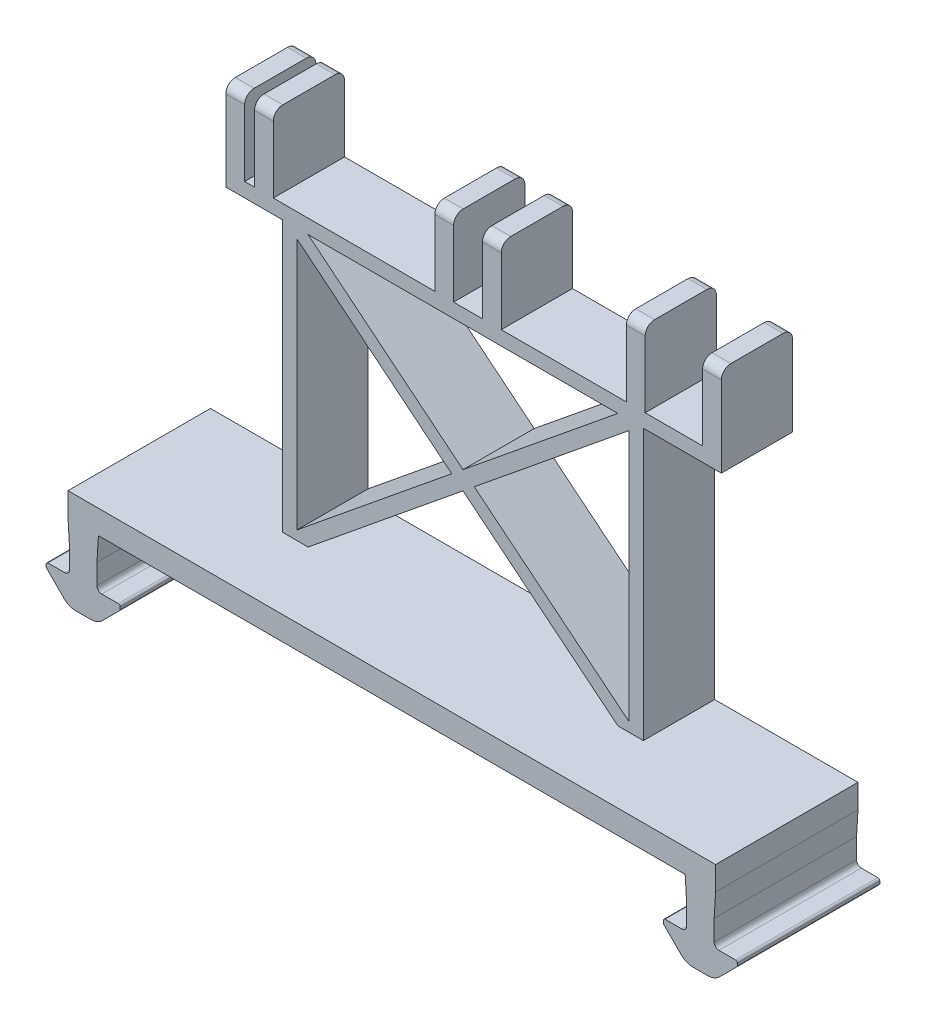
SolidWorks part; units mm, degrees
ref_plane "Front Plane" through (0, 0, 0) normal (0, 0, 1) x (1, 0, 0)
ref_plane "Top Plane" through (0, 0, 0) normal (0, 1, 0) x (1, 0, 0)
ref_plane "Right Plane" through (0, 0, 0) normal (1, 0, 0) x (0, 0, -1)
sketch "Sketch1" plane through (0, 0, 0) normal (0, 0, 1) x (1, 0, 0)
  line L7 (0, 0) -> (0, 26.663) construction
  line L8 (-2.0169, 6.858) -> (2.0169, 6.858)
  line L9 (5.3755, 8.2492) -> (10.0266, 12.9003)
  line L10 (10.287, 13.5289) -> (10.287, 14.0979)
  line L11 (9.398, 14.9869) -> (4.953, 14.9869)
  line L12 (4.064, 15.8759) -> (4.064, 27.6869)
  line L13 (0, 0) -> (20.2214, 20.2214) construction
  line L14 (-4.064, 15.8759) -> (-4.064, 27.6869)
  line L15 (-9.398, 14.9869) -> (-4.953, 14.9869)
  line L16 (-10.287, 13.5289) -> (-10.287, 14.0979)
  line L17 (-5.3755, 8.2492) -> (-10.0266, 12.9003)
  line L19 (163.0831, 6.858) -> (167.1169, 6.858)
  line L20 (170.4755, 8.2492) -> (175.1266, 12.9003)
  line L21 (175.387, 13.5289) -> (175.387, 14.0979)
  line L22 (174.498, 14.9869) -> (170.053, 14.9869)
  line L23 (169.164, 15.8759) -> (169.164, 27.6869)
  line L24 (161.036, 15.8759) -> (161.036, 27.6869)
  line L25 (155.702, 14.9869) -> (160.147, 14.9869)
  line L26 (154.813, 13.5289) -> (154.813, 14.0979)
  line L27 (159.7245, 8.2492) -> (155.0734, 12.9003)
  line L29 (-4.064, 27.6869) -> (-4.064, 34.0369)
  line L30 (-4.064, 34.0369) -> (169.164, 34.0369)
  line L31 (169.164, 34.0369) -> (169.164, 27.6869)
  line L32 (4.064, 27.6869) -> (161.036, 27.6869)
  arc A0 (10.0266, 12.9003) -> (10.287, 13.5289) centre (9.398, 13.5289) ccw
  arc A1 (9.398, 14.9869) -> (10.287, 14.0979) centre (9.398, 14.0979) cw
  arc A2 (4.953, 14.9869) -> (4.064, 15.8759) centre (4.953, 15.8759) cw
  arc A3 (2.0169, 6.858) -> (5.3755, 8.2492) centre (2.0169, 11.6078) ccw
  arc A4 (-2.0169, 6.858) -> (-5.3755, 8.2492) centre (-2.0169, 11.6078) cw
  arc A5 (-4.953, 14.9869) -> (-4.064, 15.8759) centre (-4.953, 15.8759) ccw
  arc A6 (-9.398, 14.9869) -> (-10.287, 14.0979) centre (-9.398, 14.0979) ccw
  arc A7 (-10.0266, 12.9003) -> (-10.287, 13.5289) centre (-9.398, 13.5289) cw
  arc A8 (175.1266, 12.9003) -> (175.387, 13.5289) centre (174.498, 13.5289) ccw
  arc A9 (174.498, 14.9869) -> (175.387, 14.0979) centre (174.498, 14.0979) cw
  arc A10 (170.053, 14.9869) -> (169.164, 15.8759) centre (170.053, 15.8759) cw
  arc A11 (167.1169, 6.858) -> (170.4755, 8.2492) centre (167.1169, 11.6078) ccw
  arc A12 (163.0831, 6.858) -> (159.7245, 8.2492) centre (163.0831, 11.6078) cw
  arc A13 (160.147, 14.9869) -> (161.036, 15.8759) centre (160.147, 15.8759) ccw
  arc A14 (155.702, 14.9869) -> (154.813, 14.0979) centre (155.702, 14.0979) ccw
  arc A15 (155.0734, 12.9003) -> (154.813, 13.5289) centre (155.702, 13.5289) cw
  point P1 (-4.064, 14.9869)
  point P20 (4.064, 14.9869)
  point P34 (0, 6.858)
  point P36 (161.036, 14.9869)
  point P63 (165.1, 6.858)
  dimension "D6" = 0.889
  dimension "D9" = 4.7498
  dimension "D1" = 12.7
  dimension "D2" = 4.064
  dimension "D3" = 6.858
  dimension "D4" = 10.287
  dimension "D5" = 2.032
  dimension "D7" = 0.569
  dimension "D8" = 45
  dimension "D11" = 165.1
  dimension "D12" = 6.35
  dimension "D10" = 2
extrude "Boss-Extrude2" add sketch "Sketch1" along normal blind 38.1
sketch "Sketch7" plane through (0, 0, 0) normal (0, 0, 1) x (1, 0, 0)
  line L0 (82.55, 68.2701) -> (82.55, 42.7511) construction
  line L1 (130.81, 106.4269) -> (169.164, 106.4269)
  line L3 (169.164, 34.0369) -> (-4.064, 34.0369) construction
  line L4 (-4.064, 34.0369) -> (-4.064, 15.8759) construction
  line L6 (34.29, 106.4269) -> (34.29, 34.0369)
  line L7 (34.29, 34.0369) -> (38.1, 34.0369)
  line L8 (130.81, 106.4269) -> (130.81, 34.0369)
  line L9 (-4.064, 110.2369) -> (169.164, 110.2369)
  line L10 (-4.064, 110.2369) -> (-4.064, 106.4269)
  line L11 (-4.064, 106.4269) -> (34.29, 106.4269)
  line L12 (169.164, 110.2369) -> (169.164, 106.4269)
  line L13 (38.1, 34.0369) -> (38.1, 106.4269)
  line L14 (127, 106.4269) -> (127, 34.0369)
  line L15 (38.1, 106.4269) -> (127, 106.4269)
  line L16 (127, 34.0369) -> (130.81, 34.0369)
  point P4 (82.55, 34.0369)
  point P15 (82.55, 110.2369)
  dimension "D1" = 72.39
  dimension "D2" = 3.81
  dimension "D3" = 3.81
  dimension "D4" = 44.45
extrude "Boss-Extrude6" add sketch "Sketch7" along normal blind 19.05
sketch "Sketch6" plane through (0, 110.2369, 0) normal (0, 1, 0) x (1, 0, 0)
  line L1 (19.1008, 0) -> (24.1808, 0)
  line L2 (19.1008, 0) -> (19.1008, -19.05)
  line L3 (19.1008, -19.05) -> (24.1808, -19.05)
  line L4 (24.1808, 0) -> (24.1808, -19.05)
  line L24 (169.164, 0) -> (130.81, 0) construction
  line L25 (26.7208, 0) -> (26.7208, -19.05)
  line L26 (-4.064, -38.1) -> (-4.064, 0) construction
  line L27 (26.7208, -19.05) -> (31.8008, -19.05)
  line L28 (31.8008, 0) -> (31.8008, -19.05)
  line L29 (26.7208, 0) -> (31.8008, 0)
  line L30 (75.0062, 0) -> (75.0062, -19.05)
  line L31 (75.0062, -19.05) -> (80.0862, -19.05)
  line L32 (80.0862, 0) -> (80.0862, -19.05)
  line L33 (75.0062, 0) -> (80.0862, 0)
  line L34 (87.7062, 0) -> (87.7062, -19.05)
  line L35 (87.7062, -19.05) -> (92.7862, -19.05)
  line L36 (92.7862, 0) -> (92.7862, -19.05)
  line L37 (87.7062, 0) -> (92.7862, 0)
  line L38 (126.2634, 0) -> (126.2634, -19.05)
  line L39 (126.2634, -19.05) -> (131.3434, -19.05)
  line L40 (131.3434, 0) -> (131.3434, -19.05)
  line L41 (126.2634, 0) -> (131.3434, 0)
  line L42 (146.5834, 0) -> (146.5834, -19.05)
  line L43 (146.5834, -19.05) -> (151.6634, -19.05)
  line L44 (151.6634, 0) -> (151.6634, -19.05)
  line L45 (146.5834, 0) -> (151.6634, 0)
  line L46 (-4.064, -38.1) -> (-4.064, 0) construction
  dimension "D1" = 5.08
  dimension "D2" = 19.05
  dimension "D4" = 28.2448
  dimension "D5" = 5.08
  dimension "D6" = 5.08
  dimension "D3" = 5.08
  dimension "D7" = 5.08
  dimension "D8" = 5.08
  dimension "D9" = 30.7848
  dimension "D10" = 84.1502
  dimension "D11" = 91.7702
  dimension "D12" = 150.6474
  dimension "D13" = 135.4074
extrude "Boss-Extrude5" add sketch "Sketch6" along normal blind 20.32
sketch "Sketch10" plane through (0, 0, 0) normal (0, 0, 1) x (1, 0, 0)
  line L1 (19.1008, 110.2369) -> (-4.064, 110.2369)
  line L2 (19.1008, 110.2369) -> (19.1008, 106.4269)
  line L3 (19.1008, 106.4269) -> (-4.064, 106.4269)
  line L4 (-4.064, 110.2369) -> (-4.064, 106.4269)
  line L5 (151.6634, 110.2369) -> (169.164, 110.2369)
  line L6 (151.6634, 110.2369) -> (151.6634, 106.4269)
  line L7 (151.6634, 106.4269) -> (169.164, 106.4269)
  line L8 (169.164, 110.2369) -> (169.164, 106.4269)
extrude "Cut-Extrude3" cut sketch "Sketch10" along normal up to surface (19.05 mm away) up to face at (82.6968, 107.9085, 19.05)
fillet "Fillet1" radius 2.54 12 edges at (149.1234, 130.5569, 0) (128.8034, 130.5569, 0) (149.1234, 130.5569, 19.05) (128.8034, 130.5569, 19.05) (90.2462, 130.5569, 0) (90.2462, 130.5569, 19.05) (77.5462, 130.5569, 19.05) (77.5462, 130.5569, 0) (29.2608, 130.5569, 0) (21.6408, 130.5569, 0) (21.6408, 130.5569, 19.05) (29.2608, 130.5569, 19.05)
sketch "Sketch11" plane through (0, 0, 0) normal (0, 0, 1) x (1, 0, 0)
  line L0 (38.1, 103.9702) -> (79.533, 70.2319)
  line L1 (38.1, 34.0369) -> (38.1, 106.4269) construction
  line L2 (169.164, 34.0369) -> (-4.064, 34.0369) construction
  line L3 (123.983, 34.0369) -> (127, 34.0369)
  line L4 (127, 34.0369) -> (127, 36.4936)
  line L5 (127, 106.4269) -> (127, 34.0369) construction
  line L6 (127, 36.4936) -> (85.567, 70.2319)
  line L7 (38.1, 106.4269) -> (127, 106.4269) construction
  line L8 (41.117, 106.4269) -> (38.1, 106.4269)
  line L9 (38.1, 106.4269) -> (38.1, 103.9702)
  line L10 (123.983, 106.4269) -> (127, 106.4269)
  line L11 (127, 106.4269) -> (127, 103.9702)
  line L12 (127, 103.9702) -> (85.567, 70.2319)
  line L13 (41.117, 34.0369) -> (38.1, 34.0369)
  line L14 (38.1, 34.0369) -> (38.1, 36.4936)
  line L15 (38.1, 36.4936) -> (79.533, 70.2319)
  line L16 (38.1, 34.0369) -> (127, 106.4269) construction
  line L17 (38.1, 106.4269) -> (127, 34.0369) construction
  line L18 (82.55, 67.7752) -> (41.117, 34.0369)
  line L19 (82.55, 67.7752) -> (123.983, 34.0369)
  line L20 (82.55, 72.6886) -> (123.983, 106.4269)
  line L21 (82.55, 72.6886) -> (41.117, 106.4269)
  dimension "D1" = 3.81
  dimension "D2" = 3.81
extrude "Boss-Extrude7" add sketch "Sketch11" along normal up to surface (19.05 mm away) up to face at (82.7151, 106.665, 19.05)
sketch "Sketch3" plane through (0, 0, 38.1) normal (0, 0, 1) x (1, 0, 0)
  line L27 (-3.937, 21.3369) -> (3.937, 21.3369) construction
  line L28 (4.064, 27.6869) -> (3.683, 21.3369)
  line L29 (-4.064, 27.6869) -> (-3.683, 21.3369)
  line L40 (-4.064, 34.0369) -> (-4.064, 15.8759) construction
  line L41 (-1004.064, 27.6869) -> (4.064, 27.6869) construction
  line L42 (161.036, 27.6869) -> (161.417, 21.3369)
  line L43 (169.164, 27.6869) -> (168.783, 21.3369)
  line L44 (169.164, 15.8759) -> (169.164, 34.0369) construction
  line L57 (5.1061, 8.5186) -> (9.7572, 13.1697)
  line L58 (9.906, 13.5289) -> (9.906, 14.0979)
  line L59 (9.398, 14.6059) -> (4.953, 14.6059)
  line L61 (3.683, 15.8759) -> (3.683, 28.0679)
  line L62 (3.683, 28.0679) -> (161.417, 28.0679)
  line L66 (161.417, 28.0679) -> (161.417, 15.8759)
  line L67 (160.147, 14.6059) -> (155.702, 14.6059)
  line L68 (155.194, 14.0979) -> (155.194, 13.5289)
  line L69 (155.3428, 13.1697) -> (159.9939, 8.5186)
  line L80 (163.0831, 7.239) -> (167.1169, 7.239)
  line L81 (170.2061, 8.5186) -> (174.8572, 13.1697)
  line L82 (175.006, 13.5289) -> (175.006, 14.0979)
  line L85 (174.498, 14.6059) -> (170.053, 14.6059)
  line L86 (168.783, 15.8759) -> (168.783, 33.6559)
  line L91 (168.783, 33.6559) -> (-3.683, 33.6559)
  line L93 (-3.683, 33.6559) -> (-3.683, 15.8759)
  line L95 (-4.953, 14.6059) -> (-9.398, 14.6059)
  line L97 (-9.906, 14.0979) -> (-9.906, 13.5289)
  line L99 (-9.7572, 13.1697) -> (-5.1061, 8.5186)
  line L101 (-2.0169, 7.239) -> (2.0169, 7.239)
  line L103 (5.1061, 8.5186) -> (9.7572, 13.1697)
  line L105 (9.906, 13.5289) -> (9.906, 14.0979)
  line L109 (9.398, 14.6059) -> (4.953, 14.6059)
  line L110 (3.683, 15.8759) -> (3.683, 21.3369)
  line L112 (161.417, 21.3369) -> (161.417, 15.8759)
  line L113 (160.147, 14.6059) -> (155.702, 14.6059)
  line L114 (155.194, 14.0979) -> (155.194, 13.5289)
  line L115 (155.3428, 13.1697) -> (159.9939, 8.5186)
  line L116 (163.0831, 7.239) -> (167.1169, 7.239)
  line L117 (170.2061, 8.5186) -> (174.8572, 13.1697)
  line L118 (175.006, 13.5289) -> (175.006, 14.0979)
  line L119 (174.498, 14.6059) -> (170.053, 14.6059)
  line L120 (168.783, 15.8759) -> (168.783, 21.3369)
  line L122 (-3.683, 21.3369) -> (-3.683, 15.8759)
  line L123 (-4.953, 14.6059) -> (-9.398, 14.6059)
  line L124 (-9.906, 14.0979) -> (-9.906, 13.5289)
  line L125 (-9.7572, 13.1697) -> (-5.1061, 8.5186)
  line L126 (-2.0169, 7.239) -> (2.0169, 7.239)
  line L137 (161.036, 27.6869) -> (1318.008, 27.6869) construction
  line L138 (19.1008, 130.5569) -> (24.1808, 130.5569) construction
  line L139 (24.13, 130.5569) -> (26.7716, 130.5569)
  line L140 (24.13, 130.5569) -> (24.13, 110.2369)
  line L141 (24.13, 110.2369) -> (26.7716, 110.2369)
  line L142 (26.7716, 130.5569) -> (26.7716, 110.2369)
  line L143 (126.2634, 130.5569) -> (131.3434, 130.5569) construction
  line L144 (80.0354, 130.5569) -> (87.757, 130.5569)
  line L145 (80.0354, 130.5569) -> (80.0354, 110.2369)
  line L146 (80.0354, 110.2369) -> (87.757, 110.2369)
  line L147 (87.757, 130.5569) -> (87.757, 110.2369)
  line L148 (131.2926, 130.5569) -> (146.6342, 130.5569)
  line L149 (131.2926, 130.5569) -> (131.2926, 110.2369)
  line L150 (131.2926, 110.2369) -> (146.6342, 110.2369)
  line L151 (146.6342, 130.5569) -> (146.6342, 110.2369)
  line L152 (126.2634, 110.2369) -> (92.7862, 110.2369) construction
  line L153 (24.1808, 128.0169) -> (24.1808, 110.2369) construction
  line L154 (26.7208, 128.0169) -> (26.7208, 110.2369) construction
  line L155 (80.0862, 128.0169) -> (80.0862, 110.2369) construction
  line L156 (87.7062, 128.0169) -> (87.7062, 110.2369) construction
  line L157 (5.3755, 8.2492) -> (10.0266, 12.9003)
  line L158 (10.287, 13.5289) -> (10.287, 14.0979)
  line L159 (9.398, 14.9869) -> (4.953, 14.9869)
  line L160 (4.064, 15.8759) -> (4.064, 27.6869)
  line L161 (4.064, 27.6869) -> (161.036, 27.6869)
  line L162 (161.036, 27.6869) -> (161.036, 15.8759)
  line L163 (160.147, 14.9869) -> (155.702, 14.9869)
  line L164 (154.813, 14.0979) -> (154.813, 13.5289)
  line L165 (155.0734, 12.9003) -> (159.7245, 8.2492)
  line L166 (163.0831, 6.858) -> (167.1169, 6.858)
  line L167 (170.4755, 8.2492) -> (175.1266, 12.9003)
  line L168 (175.387, 13.5289) -> (175.387, 14.0979)
  line L169 (174.498, 14.9869) -> (170.053, 14.9869)
  line L170 (169.164, 15.8759) -> (169.164, 34.0369)
  line L171 (169.164, 34.0369) -> (-4.064, 34.0369)
  line L172 (-4.064, 34.0369) -> (-4.064, 15.8759)
  line L173 (-4.953, 14.9869) -> (-9.398, 14.9869)
  line L174 (-10.287, 14.0979) -> (-10.287, 13.5289)
  line L175 (-10.0266, 12.9003) -> (-5.3755, 8.2492)
  line L176 (-2.0169, 6.858) -> (2.0169, 6.858)
  line L177 (5.3755, 8.2492) -> (10.0266, 12.9003)
  line L178 (10.287, 13.5289) -> (10.287, 14.0979)
  line L179 (9.398, 14.9869) -> (4.953, 14.9869)
  line L180 (4.064, 15.8759) -> (4.064, 27.6869)
  line L182 (161.036, 27.6869) -> (161.036, 15.8759)
  line L183 (160.147, 14.9869) -> (155.702, 14.9869)
  line L184 (154.813, 14.0979) -> (154.813, 13.5289)
  line L185 (155.0734, 12.9003) -> (159.7245, 8.2492)
  line L186 (163.0831, 6.858) -> (167.1169, 6.858)
  line L187 (170.4755, 8.2492) -> (175.1266, 12.9003)
  line L188 (175.387, 13.5289) -> (175.387, 14.0979)
  line L189 (174.498, 14.9869) -> (170.053, 14.9869)
  line L190 (169.164, 15.8759) -> (169.164, 27.6869)
  line L192 (-4.064, 27.6869) -> (-4.064, 15.8759)
  line L193 (-4.953, 14.9869) -> (-9.398, 14.9869)
  line L194 (-10.287, 14.0979) -> (-10.287, 13.5289)
  line L195 (-10.0266, 12.9003) -> (-5.3755, 8.2492)
  line L196 (-2.0169, 6.858) -> (2.0169, 6.858)
  line L197 (87.7062, 130.5569) -> (92.7862, 130.5569) construction
  line L198 (131.3434, 128.0169) -> (131.3434, 110.2369) construction
  line L199 (146.5834, 128.0169) -> (146.5834, 110.2369) construction
  arc A96 (2.0169, 7.239) -> (5.1061, 8.5186) centre (2.0169, 11.6078) ccw
  arc A97 (9.7572, 13.1697) -> (9.906, 13.5289) centre (9.398, 13.5289) ccw
  arc A98 (9.906, 14.0979) -> (9.398, 14.6059) centre (9.398, 14.0979) ccw
  arc A99 (3.683, 15.8759) -> (4.953, 14.6059) centre (4.953, 15.8759) ccw
  arc A100 (160.147, 14.6059) -> (161.417, 15.8759) centre (160.147, 15.8759) ccw
  arc A101 (155.702, 14.6059) -> (155.194, 14.0979) centre (155.702, 14.0979) ccw
  arc A102 (155.194, 13.5289) -> (155.3428, 13.1697) centre (155.702, 13.5289) ccw
  arc A103 (159.9939, 8.5186) -> (163.0831, 7.239) centre (163.0831, 11.6078) ccw
  arc A104 (167.1169, 7.239) -> (170.2061, 8.5186) centre (167.1169, 11.6078) ccw
  arc A105 (174.8572, 13.1697) -> (175.006, 13.5289) centre (174.498, 13.5289) ccw
  arc A106 (175.006, 14.0979) -> (174.498, 14.6059) centre (174.498, 14.0979) ccw
  arc A107 (168.783, 15.8759) -> (170.053, 14.6059) centre (170.053, 15.8759) ccw
  arc A108 (-4.953, 14.6059) -> (-3.683, 15.8759) centre (-4.953, 15.8759) ccw
  arc A109 (-9.398, 14.6059) -> (-9.906, 14.0979) centre (-9.398, 14.0979) ccw
  arc A110 (-9.906, 13.5289) -> (-9.7572, 13.1697) centre (-9.398, 13.5289) ccw
  arc A111 (-5.1061, 8.5186) -> (-2.0169, 7.239) centre (-2.0169, 11.6078) ccw
  arc A112 (2.0169, 7.239) -> (5.1061, 8.5186) centre (2.0169, 11.6078) ccw
  arc A113 (9.7572, 13.1697) -> (9.906, 13.5289) centre (9.398, 13.5289) ccw
  arc A114 (9.906, 14.0979) -> (9.398, 14.6059) centre (9.398, 14.0979) ccw
  arc A115 (3.683, 15.8759) -> (4.953, 14.6059) centre (4.953, 15.8759) ccw
  arc A116 (160.147, 14.6059) -> (161.417, 15.8759) centre (160.147, 15.8759) ccw
  arc A117 (155.702, 14.6059) -> (155.194, 14.0979) centre (155.702, 14.0979) ccw
  arc A118 (155.194, 13.5289) -> (155.3428, 13.1697) centre (155.702, 13.5289) ccw
  arc A119 (159.9939, 8.5186) -> (163.0831, 7.239) centre (163.0831, 11.6078) ccw
  arc A120 (167.1169, 7.239) -> (170.2061, 8.5186) centre (167.1169, 11.6078) ccw
  arc A121 (174.8572, 13.1697) -> (175.006, 13.5289) centre (174.498, 13.5289) ccw
  arc A122 (175.006, 14.0979) -> (174.498, 14.6059) centre (174.498, 14.0979) ccw
  arc A123 (168.783, 15.8759) -> (170.053, 14.6059) centre (170.053, 15.8759) ccw
  arc A124 (-4.953, 14.6059) -> (-3.683, 15.8759) centre (-4.953, 15.8759) ccw
  arc A125 (-9.398, 14.6059) -> (-9.906, 14.0979) centre (-9.398, 14.0979) ccw
  arc A126 (-9.906, 13.5289) -> (-9.7572, 13.1697) centre (-9.398, 13.5289) ccw
  arc A127 (-5.1061, 8.5186) -> (-2.0169, 7.239) centre (-2.0169, 11.6078) ccw
  arc A144 (2.0169, 6.858) -> (5.3755, 8.2492) centre (2.0169, 11.6078) ccw
  arc A145 (10.0266, 12.9003) -> (10.287, 13.5289) centre (9.398, 13.5289) ccw
  arc A146 (10.287, 14.0979) -> (9.398, 14.9869) centre (9.398, 14.0979) ccw
  arc A147 (4.064, 15.8759) -> (4.953, 14.9869) centre (4.953, 15.8759) ccw
  arc A148 (160.147, 14.9869) -> (161.036, 15.8759) centre (160.147, 15.8759) ccw
  arc A149 (155.702, 14.9869) -> (154.813, 14.0979) centre (155.702, 14.0979) ccw
  arc A150 (154.813, 13.5289) -> (155.0734, 12.9003) centre (155.702, 13.5289) ccw
  arc A151 (159.7245, 8.2492) -> (163.0831, 6.858) centre (163.0831, 11.6078) ccw
  arc A152 (167.1169, 6.858) -> (170.4755, 8.2492) centre (167.1169, 11.6078) ccw
  arc A153 (175.1266, 12.9003) -> (175.387, 13.5289) centre (174.498, 13.5289) ccw
  arc A154 (175.387, 14.0979) -> (174.498, 14.9869) centre (174.498, 14.0979) ccw
  arc A155 (169.164, 15.8759) -> (170.053, 14.9869) centre (170.053, 15.8759) ccw
  arc A156 (-4.953, 14.9869) -> (-4.064, 15.8759) centre (-4.953, 15.8759) ccw
  arc A157 (-9.398, 14.9869) -> (-10.287, 14.0979) centre (-9.398, 14.0979) ccw
  arc A158 (-10.287, 13.5289) -> (-10.0266, 12.9003) centre (-9.398, 13.5289) ccw
  arc A159 (-5.3755, 8.2492) -> (-2.0169, 6.858) centre (-2.0169, 11.6078) ccw
  arc A160 (2.0169, 6.858) -> (5.3755, 8.2492) centre (2.0169, 11.6078) ccw
  arc A161 (10.0266, 12.9003) -> (10.287, 13.5289) centre (9.398, 13.5289) ccw
  arc A162 (10.287, 14.0979) -> (9.398, 14.9869) centre (9.398, 14.0979) ccw
  arc A163 (4.064, 15.8759) -> (4.953, 14.9869) centre (4.953, 15.8759) ccw
  arc A164 (160.147, 14.9869) -> (161.036, 15.8759) centre (160.147, 15.8759) ccw
  arc A165 (155.702, 14.9869) -> (154.813, 14.0979) centre (155.702, 14.0979) ccw
  arc A166 (154.813, 13.5289) -> (155.0734, 12.9003) centre (155.702, 13.5289) ccw
  arc A167 (159.7245, 8.2492) -> (163.0831, 6.858) centre (163.0831, 11.6078) ccw
  arc A168 (167.1169, 6.858) -> (170.4755, 8.2492) centre (167.1169, 11.6078) ccw
  arc A169 (175.1266, 12.9003) -> (175.387, 13.5289) centre (174.498, 13.5289) ccw
  arc A170 (175.387, 14.0979) -> (174.498, 14.9869) centre (174.498, 14.0979) ccw
  arc A171 (169.164, 15.8759) -> (170.053, 14.9869) centre (170.053, 15.8759) ccw
  arc A172 (-4.953, 14.9869) -> (-4.064, 15.8759) centre (-4.953, 15.8759) ccw
  arc A173 (-9.398, 14.9869) -> (-10.287, 14.0979) centre (-9.398, 14.0979) ccw
  arc A174 (-10.287, 13.5289) -> (-10.0266, 12.9003) centre (-9.398, 13.5289) ccw
  arc A175 (-5.3755, 8.2492) -> (-2.0169, 6.858) centre (-2.0169, 11.6078) ccw
  dimension "D3" = 0
  dimension "D2" = 6.35
  dimension "D4" = 0.0508
  dimension "D5" = 0.0508
  dimension "D6" = 0.0508
  dimension "D7" = 0.0508
  dimension "D8" = 0.0508
  dimension "D9" = 0.0508
  dimension "D1" = 0.381
extrude "Clearance Trim" cut sketch "Sketch3" against normal up to surface (38.1 mm away)
